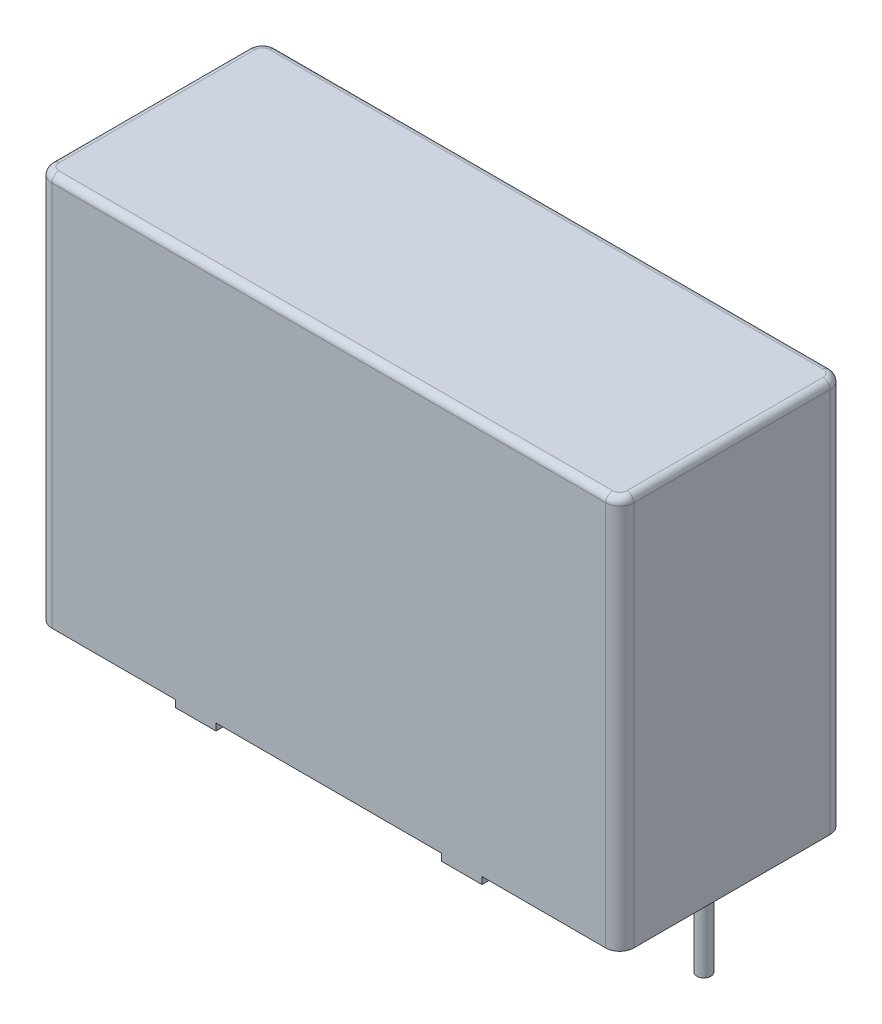
SolidWorks part; units mm, degrees
ref_plane "Спереди" through (0, 0, 0) normal (0, 0, 1) x (1, 0, 0)
ref_plane "Сверху" through (0, 0, 0) normal (0, 1, 0) x (1, 0, 0)
ref_plane "Справа" through (0, 0, 0) normal (1, 0, 0) x (0, 0, -1)
sketch "Эскиз1" plane through (0, 0, 0) normal (0, 1, 0) x (1, 0, 0)
  line L1 (-20.75, -8) -> (20.75, -8)
  line L2 (-20.75, -8) -> (-20.75, 8)
  line L3 (-20.75, 8) -> (20.75, 8)
  line L4 (20.75, -8) -> (20.75, 8)
  line L5 (-20.75, -8) -> (20.75, 8) construction
  line L6 (-20.75, 8) -> (20.75, -8) construction
  point P0 (0, 0)
extrude "Бобышка-Вытянуть1" add sketch "Эскиз1" along normal blind 28.5
fillet "Скругление1" radius 1 4 edges at (20.75, 14.25, -8) (20.75, 14.25, 8) (-20.75, 14.25, -8) (-20.75, 14.25, 8)
fillet "Скругление2" radius 0.5 8 edges at (20.4571, 28.5, 7.7071) (0, 28.5, 8) (-20.4571, 28.5, 7.7071) (-20.75, 28.5, 0) (-20.4571, 28.5, -7.7071) (0, 28.5, -8) (20.4571, 28.5, -7.7071) (20.75, 28.5, 0)
sketch "Эскиз3" plane through (0, 0, 0) normal (0, -1, 0) x (1, 0, 0)
  line L0 (-19.75, -7.5) -> (19.75, -7.5)
  line L1 (20.25, -7) -> (20.25, 7)
  line L2 (19.75, 7.5) -> (-19.75, 7.5)
  line L3 (-20.25, 7) -> (-20.25, -7)
  line L4 (-19.75, -8) -> (19.75, -8)
  line L5 (20.75, -7) -> (20.75, 7)
  line L6 (19.75, 8) -> (-19.75, 8)
  line L7 (-20.75, 7) -> (-20.75, -7)
  line L8 (-19.75, -8) -> (19.75, -8)
  line L9 (20.75, -7) -> (20.75, 7)
  line L10 (19.75, 8) -> (-19.75, 8)
  line L11 (-20.75, 7) -> (-20.75, -7)
  line L12 (0, 0) -> (0, 7.4936) construction
  line L13 (-10.9201, 8) -> (-8.0508, 8)
  line L14 (-10.9201, 8) -> (-10.9201, 7.5)
  line L15 (-10.9201, 7.5) -> (-8.0508, 7.5)
  line L16 (-8.0508, 8) -> (-8.0508, 7.5)
  line L17 (-14.6809, 0) -> (0, 0) construction
  line L18 (8.0508, 8) -> (8.0508, 7.5)
  line L19 (10.9201, 7.5) -> (8.0508, 7.5)
  line L20 (10.9201, 8) -> (10.9201, 7.5)
  line L21 (10.9201, 8) -> (8.0508, 8)
  line L22 (10.9201, -8) -> (8.0508, -8)
  line L23 (10.9201, -8) -> (10.9201, -7.5)
  line L24 (10.9201, -7.5) -> (8.0508, -7.5)
  line L25 (8.0508, -8) -> (8.0508, -7.5)
  line L26 (-8.0508, -8) -> (-8.0508, -7.5)
  line L27 (-10.9201, -7.5) -> (-8.0508, -7.5)
  line L28 (-10.9201, -8) -> (-10.9201, -7.5)
  line L29 (-10.9201, -8) -> (-8.0508, -8)
  arc A0 (19.75, -7.5) -> (20.25, -7) centre (19.75, -7) ccw
  arc A1 (20.25, 7) -> (19.75, 7.5) centre (19.75, 7) ccw
  arc A2 (-19.75, 7.5) -> (-20.25, 7) centre (-19.75, 7) ccw
  arc A3 (-20.25, -7) -> (-19.75, -7.5) centre (-19.75, -7) ccw
  arc A4 (19.75, -8) -> (20.75, -7) centre (19.75, -7) ccw
  arc A5 (20.75, 7) -> (19.75, 8) centre (19.75, 7) ccw
  arc A6 (-19.75, 8) -> (-20.75, 7) centre (-19.75, 7) ccw
  arc A7 (-20.75, -7) -> (-19.75, -8) centre (-19.75, -7) ccw
  arc A8 (19.75, -8) -> (20.75, -7) centre (19.75, -7) ccw
  arc A9 (20.75, 7) -> (19.75, 8) centre (19.75, 7) ccw
  arc A10 (-19.75, 8) -> (-20.75, 7) centre (-19.75, 7) ccw
  arc A11 (-20.75, -7) -> (-19.75, -8) centre (-19.75, -7) ccw
  dimension "D1" = 0
  dimension "D2" = 0.5
extrude "Вырез-Вытянуть1" cut sketch "Эскиз3" against normal blind 0.5 contours L3 A3 L0 A0 L1 A1 L2 A2 | A3 L3 A2 L2 L14 L18 L19 L20 L21 L13 L28 L0 | L18 L10 L16 L2 | A1 L1 A0 L0 L23 L13 L14 L15 L16 L18 L20 L2 | L26 L8 L25 L0
sketch "Эскиз4" plane through (0, 0.5, 0) normal (0, -1, 0) x (1, 0, 0)
  line L0 (0, 0) -> (0, 3.6215) construction
  circle A0 centre (-18.75, 0) radius 0.5
  circle A1 centre (18.75, 0) radius 0.5
  dimension "D1" = 37.5
extrude "Бобышка-Вытянуть2" add sketch "Эскиз4" along normal blind 6
